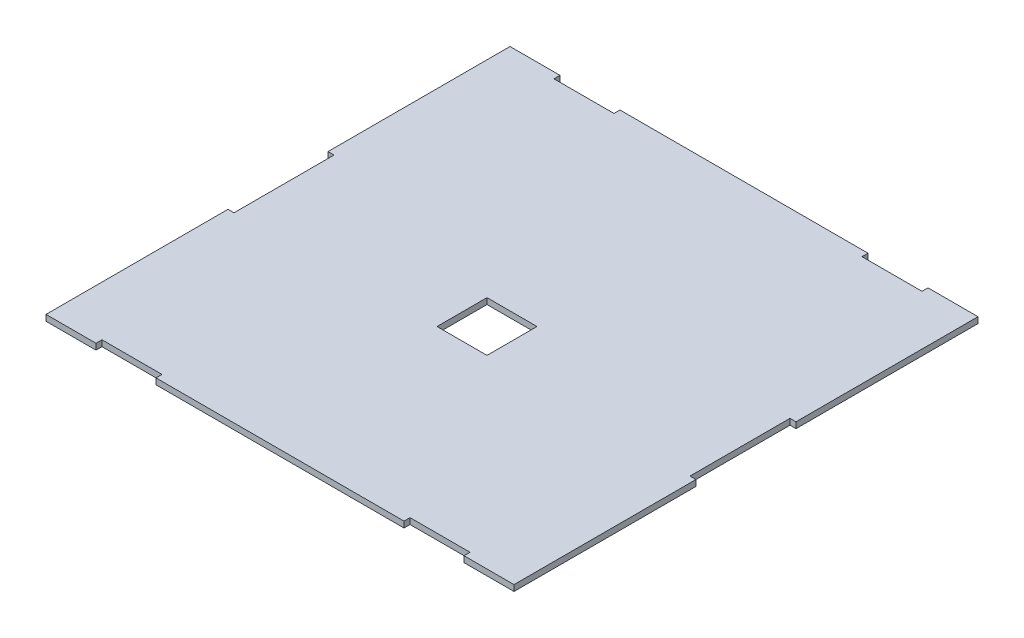
SolidWorks part; units mm, degrees
material "Teca"
ref_plane "Plano frontal" through (0, 0, 0) normal (0, 0, 1) x (1, 0, 0)
ref_plane "Plano superior" through (0, 0, 0) normal (0, 1, 0) x (1, 0, 0)
ref_plane "Plano direito" through (0, 0, 0) normal (1, 0, 0) x (0, 0, -1)
sketch "Esboço1" plane through (0, 0, 0) normal (0, 1, 0) x (1, 0, 0)
  line L0 (0, 0) -> (0, 91)
  line L1 (0, 91) -> (3, 91)
  line L2 (3, 91) -> (3, 141)
  line L3 (3, 141) -> (0, 141)
  line L4 (0, 141) -> (0, 232)
  line L6 (234, 232) -> (234, 141)
  line L7 (234, 141) -> (231, 141)
  line L8 (231, 141) -> (231, 91)
  line L9 (231, 91) -> (234, 91)
  line L10 (234, 91) -> (234, 0)
  line L11 (234, 0) -> (209, 0)
  line L12 (0, 232) -> (234, 232)
  line L13 (103, 117.5) -> (128, 117.5)
  line L14 (103, 117.5) -> (103, 92.5)
  line L15 (103, 92.5) -> (128, 92.5)
  line L16 (128, 117.5) -> (128, 92.5)
  line L19 (25, 0) -> (25, 3)
  line L20 (25, 3) -> (55, 3)
  line L21 (55, 0) -> (55, 3)
  line L22 (25, 0) -> (0, 0)
  line L23 (179, 0) -> (55, 0)
  line L25 (209, 0) -> (209, 3)
  line L26 (209, 3) -> (179, 3)
  line L27 (179, 0) -> (179, 3)
  line L29 (25, 232) -> (55, 232)
  line L30 (25, 232) -> (25, 229)
  line L31 (25, 229) -> (55, 229)
  line L32 (55, 232) -> (55, 229)
  line L33 (179, 232) -> (209, 232)
  line L34 (179, 232) -> (179, 229)
  line L35 (179, 229) -> (209, 229)
  line L36 (209, 232) -> (209, 229)
  dimension "D1" = 50
  dimension "D2" = 50
  dimension "D3" = 3
  dimension "D4" = 3
  dimension "D5" = 91
  dimension "D6" = 91
  dimension "D7" = 91
  dimension "D8" = 234
  dimension "D9" = 234
  dimension "D10" = 25
  dimension "D11" = 25
  dimension "D12" = 103
  dimension "D13" = 25
  dimension "D14" = 25
  dimension "D15" = 30
  dimension "D16" = 3
  dimension "D17" = 30
  dimension "D18" = 3
  dimension "D19" = 25
  dimension "D20" = 30
  dimension "D21" = 3
  dimension "D22" = 30
  dimension "D23" = 3
  dimension "D24" = 25
extrude "Ressalto-extrusão3" add sketch "Esboço1" along normal blind 3 contours L11 L10 L9 L8 L7 L6 L12 L4 L3 L2 L1 L0 L13 L16 L15 L14
